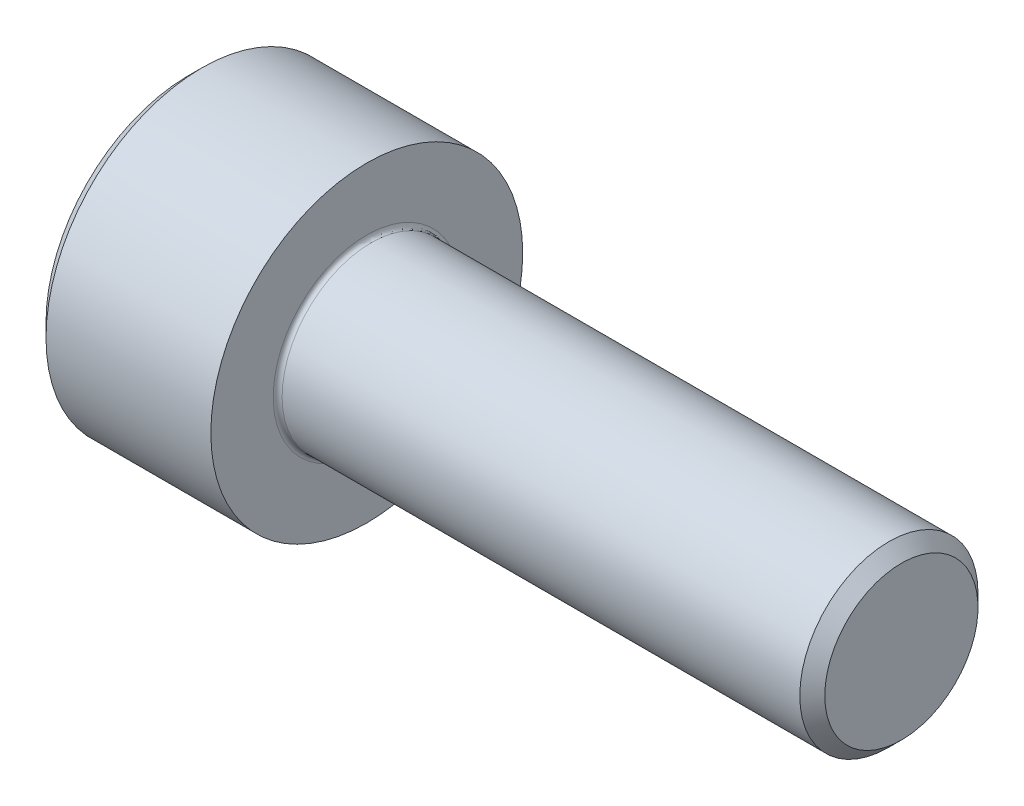
SolidWorks part; units mm, degrees
material "Galvanized Steel"
ref_plane "Plane1" through (0, 0, 0) normal (0, 0, 1) x (1, 0, 0)
ref_plane "Plane2" through (0, 0, 0) normal (0, 1, 0) x (1, 0, 0)
ref_plane "Plane3" through (0, 0, 0) normal (1, 0, 0) x (0, 0, -1)
sketch "BodySke" plane through (0, 0, 0) normal (0, 0, 1) x (1, 0, 0)
  line L0 (0, 0) -> (0, 3.5)
  line L1 (0, 3.5) -> (4, 3.5)
  line L2 (4, 3.5) -> (4, 2)
  line L3 (4, 2) -> (15.7195, 2)
  line L4 (16, 1.7195) -> (16, 0)
  line L5 (16, 0) -> (0, 0)
  line L6 (-31.75, 0) -> (127, 0) construction
  line L8 (16, 1.7195) -> (15.7195, 2)
  line L10 (16, -1.7195) -> (15.7195, -2) construction
  line L11 (4.5, 9.525) -> (4.5, 3.175) construction
  line L12 (-4, 9.525) -> (-4, 3.175) construction
  line L13 (-44, 9.525) -> (-44, 3.175) construction
  dimension "Head_ht" = 4
  dimension "Length" = 12
  dimension "Body_ch_ang" = 45
  dimension "Diameter" = 4
  dimension "Minor_dia" = 3.439
  dimension "Advance" = 0.5
  dimension "Thread_nom" = 20
  dimension "Thread_length" = 60
  dimension "Head_dia" = 7
revolve "Base-Revolve" add sketch "BodySke"
cosmetic thread "ThreadCosmetic" [suppressed]
fillet "Fillet1" radius 0.1 1 edges at (4, 0, 2)
sketch "Sketch2" plane through (0, 0, 0) normal (0, 0, 1) x (1, 0, 0)
  line L0 (0, 1.5) -> (1.3, 1.5)
  line L1 (1.3, 1.5) -> (2.166, 0)
  line L2 (-31.75, 0) -> (127, 0) construction
  line L3 (2.166, 0) -> (0, 0)
  line L4 (0, 0) -> (0, 1.5)
  line L6 (0, 0) -> (47.625, 0) construction
  dimension "D1" = 1.5
  dimension "D2" = 60
  dimension "Depth" = 1.3
revolve "Hex-PreBroach" cut sketch "Sketch2" angle 360 about L6
sketch "Sketch3" plane through (0, 0, 0) normal (-1, 0, 0) x (0, 0.5, 0.866)
  line L0 (0.866, 1.5) -> (-0.866, 1.5)
  line L1 (-0.866, 1.5) -> (-1.7321, 0)
  line L2 (0.866, 1.5) -> (1.7321, 0)
  line L3 (0.866, -1.5) -> (1.7321, 0)
  line L4 (0.866, -1.5) -> (-0.866, -1.5)
  line L5 (-0.866, -1.5) -> (-1.7321, 0)
  dimension "D1" = 1.5
  dimension "D2" = 1.5
  dimension "Hex_size" = 3
extrude "Hex" cut sketch "Sketch3" against normal blind 1.3
chamfer "Chamfer1" distance 0.3 angle 45 1 edges at (0, 0, 3.5)
sketch "Sketch4" plane through (0, 0, 0) normal (0, 1, 0) x (1, 0, 0)
  line L0 (0, 1.778) -> (1.0265, 0)
  line L1 (0, 3.2) -> (0, -3.2) construction
  line L2 (1.3, 0) -> (0, 0) construction
  line L3 (1.0265, 0) -> (0, 0)
  line L4 (0, 0) -> (0, 1.778)
  line L5 (2.166, 0) -> (1.3, 1.5) construction
  line L6 (1.0265, 0) -> (2.166, 0) construction
  dimension "D1" = 3.556
revolve "Cut-Revolve1" cut sketch "Sketch4" angle 360 about L6
equation "\"D2@Sketch3\" = \"Hex_size@Sketch3\" / 2"
equation "\"D1@Sketch3\" = \"Hex_size@Sketch3\" / 2"
equation "\"D1@Sketch2\" = \"Hex_size@Sketch3\" / 2"
equation "\"Thread_minor@ThreadCosmetic\"  =  \"Minor_dia@BodySke\""
equation "\"Depth@Sketch2\" =  \"Key_eng@Hex\""
equation "\"Thread_length@ThreadCosmetic\" = ((sgn( (\"Length@BodySke\" - \"Advance@BodySke\" * 3.0) - \"Thread_nom@BodySke\" )-1)*( (\"Length@BodySke\" - \"Advance@BodySke\" * 3.0) - \"Thread_nom@BodySke\" ))/-2+ \"Thread_nom@BodySke\""
